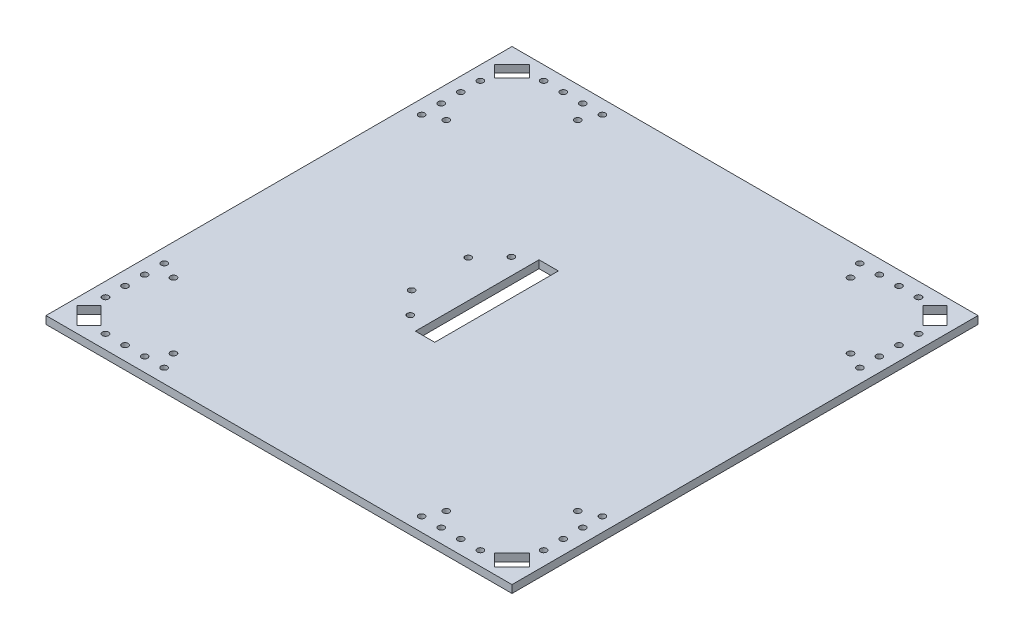
SolidWorks part; units mm, degrees
material "1060 Alloy"
ref_plane "Front Plane" through (0, 0, 0) normal (0, 0, 1) x (1, 0, 0)
ref_plane "Top Plane" through (0, 0, 0) normal (0, 1, 0) x (1, 0, 0)
ref_plane "Right Plane" through (0, 0, 0) normal (1, 0, 0) x (0, 0, -1)
sketch "Sketch1" plane through (0, 0, 0) normal (0, 1, 0) x (1, 0, 0)
  line L1 (-150.8125, -150.8125) -> (150.8125, -150.8125)
  line L2 (-150.8125, -150.8125) -> (-150.8125, 150.8125)
  line L3 (-150.8125, 150.8125) -> (150.8125, 150.8125)
  line L4 (150.8125, -150.8125) -> (150.8125, 150.8125)
  line L5 (-150.8125, -150.8125) -> (150.8125, 150.8125) construction
  line L6 (-150.8125, 150.8125) -> (150.8125, -150.8125) construction
  point P0 (0, 0)
  dimension "D1" = 301.625
extrude "Boss-Extrude1" add sketch "Sketch1" along normal blind 5
sketch "Sketch2" plane through (0, 0, 0) normal (0, -1, 0) x (1, 0, 0)
  line L0 (127.4206, 138.7343) -> (138.7343, 127.4206)
  line L1 (138.7343, 127.4206) -> (146.5125, 135.1988)
  line L2 (146.5125, 135.1988) -> (135.1988, 146.5125)
  line L3 (135.1988, 146.5125) -> (127.4206, 138.7343)
  line L4 (150.8125, 144.8125) -> (150.8125, 129.2335) construction
  line L5 (129.2335, 150.8125) -> (144.8125, 150.8125) construction
  line L6 (146.5125, -135.1988) -> (138.7343, -127.4206)
  line L7 (138.7343, -127.4206) -> (127.4206, -138.7343)
  line L8 (127.4206, -138.7343) -> (135.1988, -146.5125)
  line L9 (135.1988, -146.5125) -> (146.5125, -135.1988)
  line L10 (-135.1988, -146.5125) -> (-127.4206, -138.7343)
  line L11 (-127.4206, -138.7343) -> (-138.7343, -127.4206)
  line L12 (-138.7343, -127.4206) -> (-146.5125, -135.1988)
  line L13 (-146.5125, -135.1988) -> (-135.1988, -146.5125)
  line L14 (-146.5125, 135.1988) -> (-138.7343, 127.4206)
  line L15 (-138.7343, 127.4206) -> (-127.4206, 138.7343)
  line L16 (-127.4206, 138.7343) -> (-135.1988, 146.5125)
  line L17 (-135.1988, 146.5125) -> (-146.5125, 135.1988)
  line L18 (0, 0) -> (138.7343, 127.4206) construction
  line L19 (0, 0) -> (127.4206, -138.7343) construction
  line L20 (-150.8125, -150.8125) -> (-150.8125, 150.8125) construction
  point P27 (-150.8125, 0)
  dimension "D1" = 45
  dimension "D2" = 4.3
  dimension "D3" = 4.3
  dimension "D4" = 16
  dimension "D5" = 11
  dimension "D7" = 90
  dimension "D8" = 188.3699
  dimension "D6" = 4
extrude "Cut-Extrude1" cut sketch "Sketch2" against normal blind 10
sketch "Sketch4" plane through (0, 5, 0) normal (0, 1, 0) x (1, 0, 0)
  line L1 (-22.5, 40) -> (-10, 40)
  line L2 (-22.5, 40) -> (-22.5, -40)
  line L3 (-22.5, -40) -> (-10, -40)
  line L4 (-10, 40) -> (-10, -40)
  dimension "D1" = 40
  dimension "D2" = 40
  dimension "D3" = 12.5
  dimension "D4" = 10
extrude "Cut-Extrude3" cut sketch "Sketch4" against normal through all
sketch "Sketch5" plane through (0, 5, 0) normal (0, 1, 0) x (1, 0, 0)
  circle A0 centre (-130.8125, 88.3125) radius 2 construction
  circle A1 centre (-141.8125, 95.9792) radius 2 construction
  circle A2 centre (-141.8125, 83.3125) radius 2 construction
  circle A3 centre (-130.8125, 88.3125) radius 2
  circle A4 centre (-141.8125, 95.9792) radius 2
  circle A5 centre (-141.8125, 83.3125) radius 2
  circle A6 centre (-141.8125, 108.6458) radius 2 construction
  circle A7 centre (-141.8125, 108.6458) radius 2
  circle A8 centre (-141.8125, 121.3125) radius 2 construction
  circle A9 centre (-141.8125, 121.3125) radius 2
extrude "Cut-Extrude4" cut sketch "Sketch5" against normal blind 10
ref_plane "Plane17" through (0, 0, 0) normal (-0.7071, 0, 0.7071) x (0.7071, 0, 0.7071)
mirror "Mirror1" about plane through (0, 0, 0) normal (-0.7071, 0, 0.7071) of "Cut-Extrude4"
mirror "Mirror2" about plane through (0, 0, 0) normal (0, 0, 1) of "Mirror1", "Cut-Extrude4"
mirror "Mirror3" about plane through (0, 0, 0) normal (1, 0, 0) of "Mirror1", "Cut-Extrude4", "Mirror2"
sketch "Sketch6" plane through (0, 5, 0) normal (0, 1, 0) x (1, 0, 0)
  circle A4 centre (-33.1225, -32.7) radius 2
  circle A5 centre (-46.6225, -18.3) radius 2
  circle A6 centre (-46.6225, 18.3) radius 2
  circle A7 centre (-33.1225, 32.7) radius 2
extrude "Cut-Extrude5" cut sketch "Sketch6" against normal through all
equation "\"D3@Sketch2\"=\"D2@Sketch2\""
